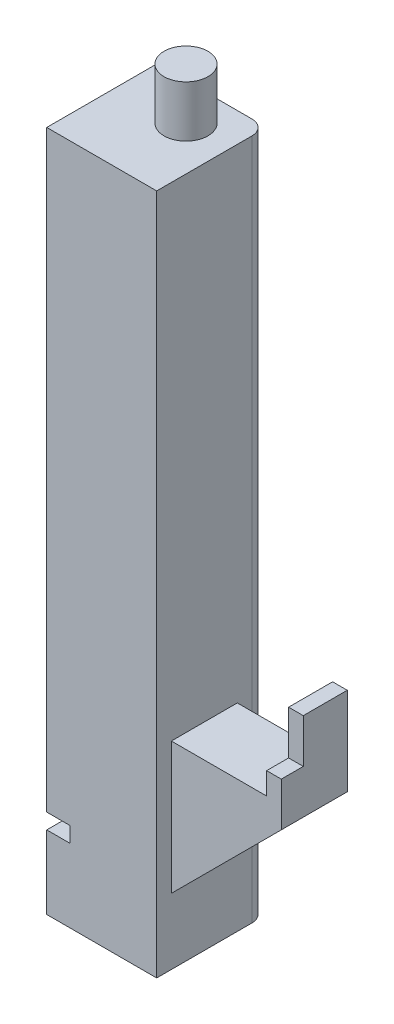
SolidWorks part; units mm, degrees
ref_plane "Front Plane" through (0, 0, 0) normal (0, 0, 1) x (1, 0, 0)
ref_plane "Top Plane" through (0, 0, 0) normal (0, 1, 0) x (1, 0, 0)
ref_plane "Right Plane" through (0, 0, 0) normal (1, 0, 0) x (0, 0, -1)
sketch "Sketch1" plane through (0, 0, 0) normal (0, 1, 0) x (1, 0, 0)
  line L0 (-68.486, 0) -> (57.6746, 0) construction
  line L1 (0, 62.7099) -> (0, -58.019) construction
  line L3 (-7.5, -7.5) -> (7.5, -7.5)
  line L4 (-7.5, -7.5) -> (-7.5, 7.5)
  line L5 (-7.5, 7.5) -> (7.5, 7.5)
  line L6 (7.5, -7.5) -> (7.5, 7.5)
  line L7 (-7.5, -7.5) -> (7.5, 7.5) construction
  line L8 (-7.5, 7.5) -> (7.5, -7.5) construction
  point P5 (0, 0)
  dimension "D1" = 15
  dimension "D2" = 15
extrude "Boss-Extrude1" add sketch "Sketch1" along normal blind 93
sketch "Sketch2" plane through (0, 93, 0) normal (0, 1, 0) x (1, 0, 0)
  line L0 (7.5, -7.5) -> (7.5, 7.5) construction
  line L2 (7.5, 7.5) -> (-7.5, 7.5) construction
  circle A0 centre (1.5, 2.5) radius 3
  dimension "D1" = 6
  dimension "D2" = 6
  dimension "D3" = 5
extrude "Boss-Extrude2" add sketch "Sketch2" along normal blind 7
sketch "Sketch3" plane through (0, 0, 7.5) normal (0, 0, 1) x (1, 0, 0)
  line L0 (-7.5, 12.1) -> (-4.3, 12.1)
  line L1 (-7.5, 93) -> (-7.5, 0) construction
  line L2 (-4.3, 12.1) -> (-4.3, 10)
  line L3 (-4.3, 10) -> (-7.5, 10)
  line L4 (-7.5, 10) -> (-7.5, 12.1)
  dimension "D1" = 10
  dimension "D2" = 2.1
  dimension "D3" = 3.2
extrude "Cut-Extrude1" cut sketch "Sketch3" against normal through all
fillet "Fillet1" radius 2 1 edges at (7.5, 46.5, -7.5)
sketch "Sketch4" plane through (0, 0, 7.5) normal (0, 0, 1) x (1, 0, 0)
  line L0 (17.4849, 0) -> (-14.6971, 0) construction
  line L1 (7.5, 24) -> (22.5, 24)
  line L2 (22.5, 24) -> (22.5, 36)
  line L3 (22.5, 36) -> (20.5, 36)
  line L4 (20.5, 36) -> (20.5, 27)
  line L5 (20.5, 27) -> (7.5, 27)
  line L6 (7.5, 93) -> (7.5, 0) construction
  line L7 (7.5, 27) -> (7.5, 24)
  point P14 (0, 0)
  point P15 (0, 0)
  dimension "D1" = 3
  dimension "D2" = 15
  dimension "D3" = 2
  dimension "D4" = 12
  dimension "D5" = 24
extrude "Boss-Extrude3" add sketch "Sketch4" against normal blind 6 from offset 5 offset against normal yes
sketch "Sketch5" plane through (0, 0, 2.5) normal (0, 0, 1) x (1, 0, 0)
  line L0 (20.5, 30) -> (22.5, 30)
  line L6 (7.5, 27) -> (7.5, 24)
  line L7 (7.5, 24) -> (22.5, 24)
  line L8 (22.5, 24) -> (22.5, 36)
  line L9 (22.5, 36) -> (20.5, 36)
  line L10 (20.5, 36) -> (20.5, 27)
  line L11 (20.5, 27) -> (7.5, 27)
  line L12 (7.5, 27) -> (7.5, 24)
  line L13 (7.5, 24) -> (22.5, 24)
  line L14 (22.5, 24) -> (22.5, 30)
  line L16 (20.5, 30) -> (20.5, 27)
  line L17 (20.5, 27) -> (7.5, 27)
  dimension "D2" = 6
  dimension "D1" = 0
extrude "Boss-Extrude4" add sketch "Sketch5" along normal blind 3
sketch "Sketch6" plane through (0, 0, 5.5) normal (0, 0, 1) x (1, 0, 0)
  line L0 (22.5, 24) -> (7.5, 24)
  line L1 (7.5, 24) -> (7.5, 9)
  line L2 (7.5, 93) -> (7.5, 0) construction
  line L3 (7.5, 9) -> (22.5, 24)
  dimension "D1" = 45
extrude "Boss-Extrude5" add sketch "Sketch6" against normal up to surface (9 mm away) up to face at (16.8333, 29, -3.5)
